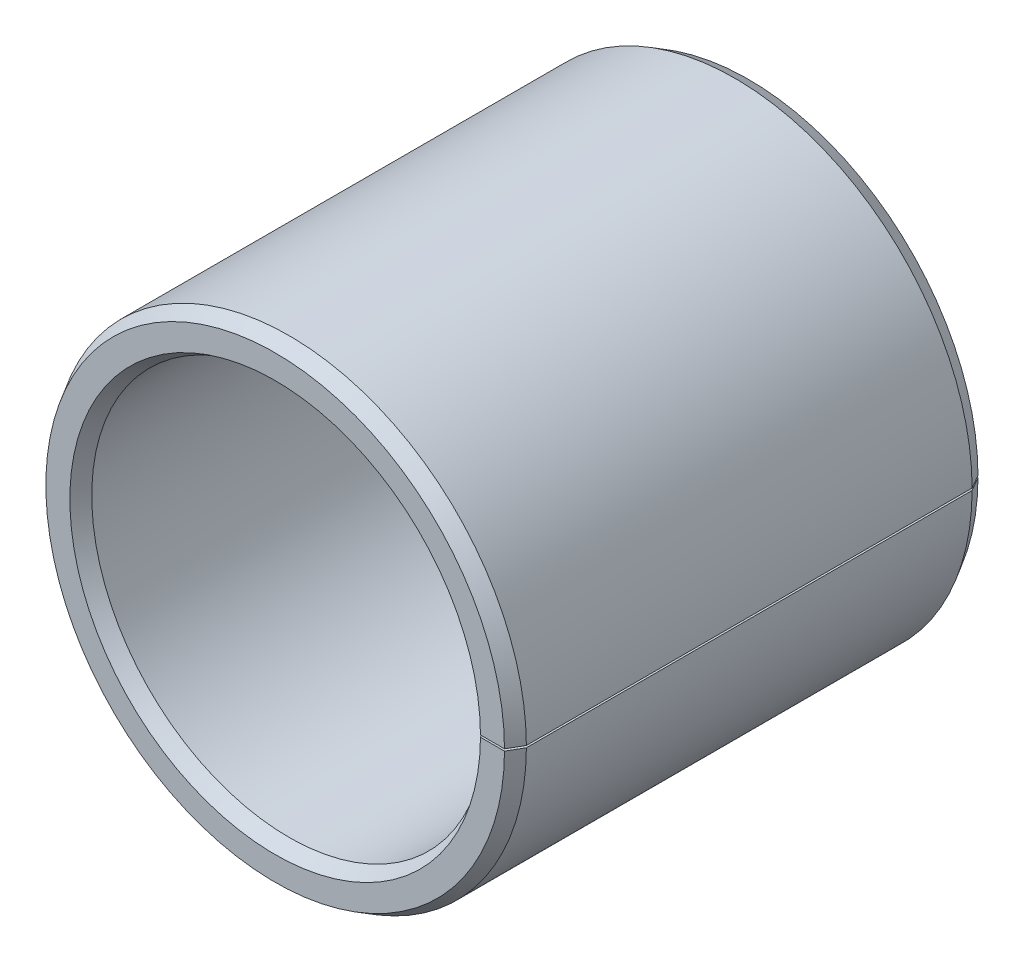
SolidWorks part; units mm, degrees
ref_plane "Front Plane" through (0, 0, 0) normal (0, 0, 1) x (1, 0, 0)
ref_plane "Top Plane" through (0, 0, 0) normal (0, 1, 0) x (1, 0, 0)
ref_plane "Right Plane" through (0, 0, 0) normal (1, 0, 0) x (0, 0, -1)
sketch "Sketch1" plane through (0, 0, 0) normal (0, 0, 1) x (1, 0, 0)
  line L0 (-5, 0) -> (5, 0) construction
  line L1 (-6.015, 0) -> (6.015, 0) construction
  point P4 (0, 0)
  point P8 (0, 0)
  dimension "ID" = 10
  dimension "OD" = 12.03
sketch "Sketch2" plane through (0, 0, 0) normal (1, 0, 0) x (0, 0, -1)
  line L0 (0, -6.015) -> (0, 6.015) construction
  line L3 (-6, 6.015) -> (6, 6.015) construction
  point P7 (0, 0)
  point P10 (0, 6.015)
  dimension "D1" = 12.03
  dimension "Length" = 12
sketch "Sketch3" plane through (0, 0, 0) normal (1, 0, 0) x (0, 0, -1)
  line L0 (-6, 5) -> (6, 5)
  line L2 (6, 5) -> (6, 6.015)
  line L3 (6, 6.015) -> (-6, 6.015)
  line L4 (-6, 6.015) -> (-6, 5)
  line L5 (-6, 0) -> (6, 0) construction
  line L6 (6, -5) -> (6, 5) construction
  point P9 (6, 0)
  point P19 (0, 0)
  dimension "D1" = 10
revolve "Revolve1" add sketch "Sketch3" angle 360 about L5
chamfer "Chamfer1" distance 0.203 angle 60 2 edges at (0, -6.015, -6) (0, -5, 6)
chamfer "Chamfer2" distance 0.203 angle 60 2 edges at (0, -5, -6) (0, -6.015, 6)
sketch "Sketch4" plane through (0, 0, 0) normal (1, 0, 0) x (0, 0, -1)
  line L0 (-6, 0) -> (6, 0) construction
  line L2 (-5.6484, 6.015) -> (-5.6484, -6.015) construction
  line L3 (5.6484, 6.015) -> (5.6484, -6.015) construction
  point P13 (-5.6484, 0)
  point P14 (5.6484, 0)
  point P18 (0, 0)
sketch "Sketch5" plane through (0, 0, 0) normal (0, 0, 1) x (1, 0, 0)
  circle A0 centre (0, 0) radius 5.203
  circle A3 centre (0, 0) radius 5.203 construction
extrude "Cut-Extrude1" cut sketch "Sketch5" against normal up to vertex (5.6484 mm away) and the other way up to vertex (5.6484 mm away) up to point (0, 0, -5.6484) other way up to point (0, 0, 5.6484)
sketch "Sketch6" plane through (0, 0, 0) normal (0, 0, 1) x (1, 0, 0)
  circle A0 centre (0, 0) radius 5.203
  circle A1 centre (0, 0) radius 5
  circle A2 centre (0, 0) radius 5.203 construction
  circle A3 centre (0, 0) radius 5 construction
extrude "Boss-Extrude1" add sketch "Sketch6" along normal up to vertex (5.6484 mm away) and the other way up to vertex (5.6484 mm away) separate body up to point (0, 0, 5.6484) other way up to point (0, 0, -5.6484)
sketch "Sketch7" plane through (0, 0, 0) normal (0, 0, 1) x (1, 0, 0)
  line L0 (0, -0.025) -> (0, 0.025)
  line L1 (0, 0.025) -> (6.015, 0.025)
  line L2 (6.015, 0.025) -> (6.015, -0.025)
  line L3 (6.015, -0.025) -> (0, -0.025)
  line L4 (-6.015, 0) -> (6.015, 0) construction
  point P4 (0, 0)
  point P10 (0, 0)
  dimension "D1" = 0.05
  dimension "D2" = 12.03
extrude "Cut-Extrude2" cut sketch "Sketch7" against normal through all both and the other way through all
equation "\"D1@Chamfer1\" = ( ( \"OD@Sketch1\" - \"ID@Sketch1\" ) / 2 ) * .2"
equation "\"D1@Chamfer2\" = \"D1@Chamfer1\""
equation "\"D2@Sketch7\"= \"OD@Sketch1\""
equation "\"D1@Sketch2\" = \"OD@Sketch1\""
equation "\"D1@Sketch3\"=\"ID@Sketch1\""
